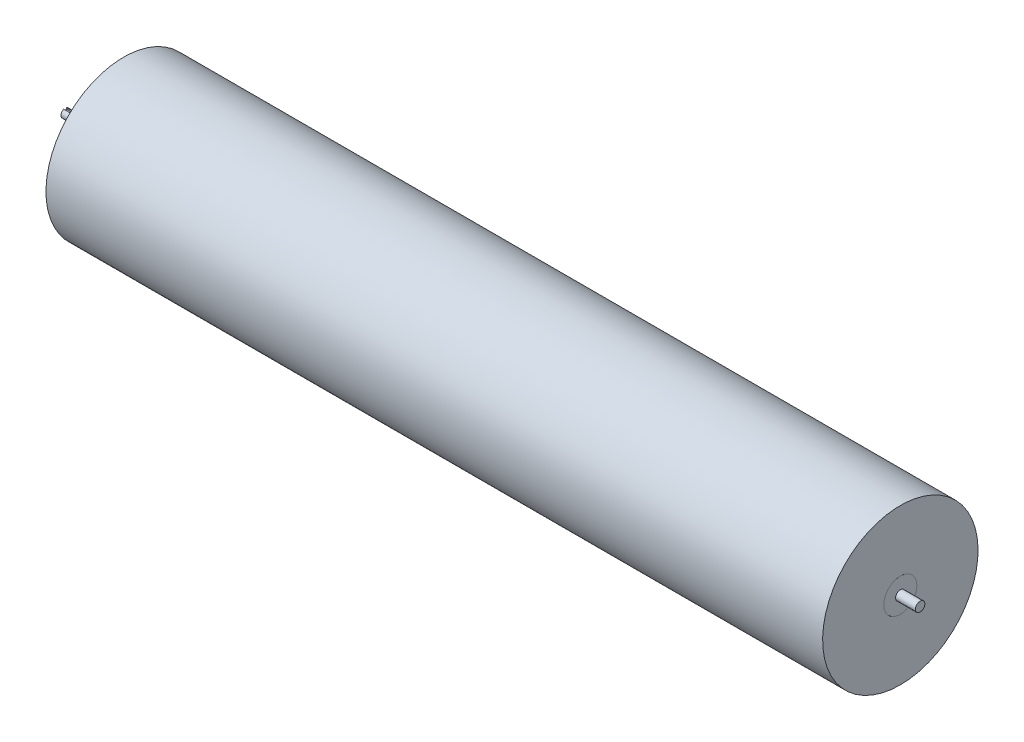
SolidWorks part; units mm, degrees
material "AISI 304"
ref_plane "Front Plane" through (0, 0, 0) normal (0, 0, 1) x (1, 0, 0)
ref_plane "Top Plane" through (0, 0, 0) normal (0, 1, 0) x (1, 0, 0)
ref_plane "Right Plane" through (0, 0, 0) normal (1, 0, 0) x (0, 0, -1)
sketch "Sketch1" plane through (0, 0, 0) normal (0, 0, 1) x (1, 0, 0)
  line L0 (-824.5, 165) -> (824.5, 165)
  line L1 (824.5, 165) -> (824.5, 35.1005)
  line L2 (824.5, 35.1005) -> (-824.5, 35.1005)
  line L3 (-824.5, 35.1005) -> (-824.5, 165)
  line L4 (-824.5, 0) -> (824.5, 0) construction
  point P8 (0, 0)
  dimension "D1" = 1649
  dimension "D2" = 330
  dimension "D3" = 70.201
revolve "Revolve1" add sketch "Sketch1" angle 360 about L4
sketch "Sketch2" plane through (-824.5, 0, 0) normal (-1, 0, 0) x (0, 0, 1)
  circle A1 centre (0, 0) radius 35.1
  circle A2 centre (0, 0) radius 10.0005
  dimension "D1" = 20.001
  dimension "D2" = 70.2
extrude "Boss-Extrude1" add sketch "Sketch2" against normal blind 10
sketch "Sketch3" plane through (824.5, 0, 0) normal (1, 0, 0) x (0, 0, -1)
  circle A0 centre (0, 0) radius 10.0005 construction
  circle A1 centre (0, 0) radius 35.1
  circle A2 centre (0, 0) radius 35.1
  circle A3 centre (0, 0) radius 10.0005
  dimension "D1" = 0
extrude "Boss-Extrude2" add sketch "Sketch3" against normal blind 10 separate body
sketch "Sketch4" plane through (0, 0, 0) normal (0, 0, 1) x (1, 0, 0)
  line L0 (-866.5, 10) -> (866.5, 10)
  line L1 (-824.5, 10.0005) -> (-824.5, -10.0005) construction
  line L6 (866.5, 0) -> (-948.8, 0) construction
  line L8 (-824.5, 10.0005) -> (-824.5, -10.0005) construction
  line L9 (-866.5, 10) -> (-866.5, 9)
  line L10 (-948.8, 0) -> (866.5, 0) construction
  line L11 (-948.8, 0) -> (866.5, 0)
  line L14 (866.5, 10) -> (866.5, 0)
  line L15 (-866.5, 9) -> (-948.8, 9)
  line L16 (-948.8, 9) -> (-948.8, 0)
  line L17 (-824.5, 35.1) -> (-824.5, -35.1) construction
  line L18 (824.5, -35.1) -> (824.5, 35.1) construction
  point P17 (866.5, 5)
  dimension "D1" = 18
  dimension "D2" = 42
  dimension "D3" = 82.3
  dimension "D5" = 42
  dimension "D7" = 20
revolve "Revolve3" add sketch "Sketch4" angle 360 about L11
ref_plane "Plane1" through (0, 9, 0) normal (0, 1, 0) x (1, 0, 0)
sketch "Sketch5" plane through (0, 9, 0) normal (0, 1, 0) x (1, 0, 0)
  line L0 (-948.8, 3) -> (-898.8, 3)
  line L1 (-948.8, 9) -> (-948.8, -9) construction
  line L2 (-898.8, -3) -> (-948.8, -3)
  line L3 (-948.8, -3) -> (-948.8, 3)
  line L4 (-948.8, 9) -> (-948.8, -9) construction
  arc A0 (-898.8, 3) -> (-898.8, -3) centre (-898.8, 0) cw
  point P6 (-948.8, 0)
  point P8 (-948.8, 0)
  dimension "D1" = 6
  dimension "D2" = 50
extrude "Cut-Extrude1" cut sketch "Sketch5" against normal blind 3.5
